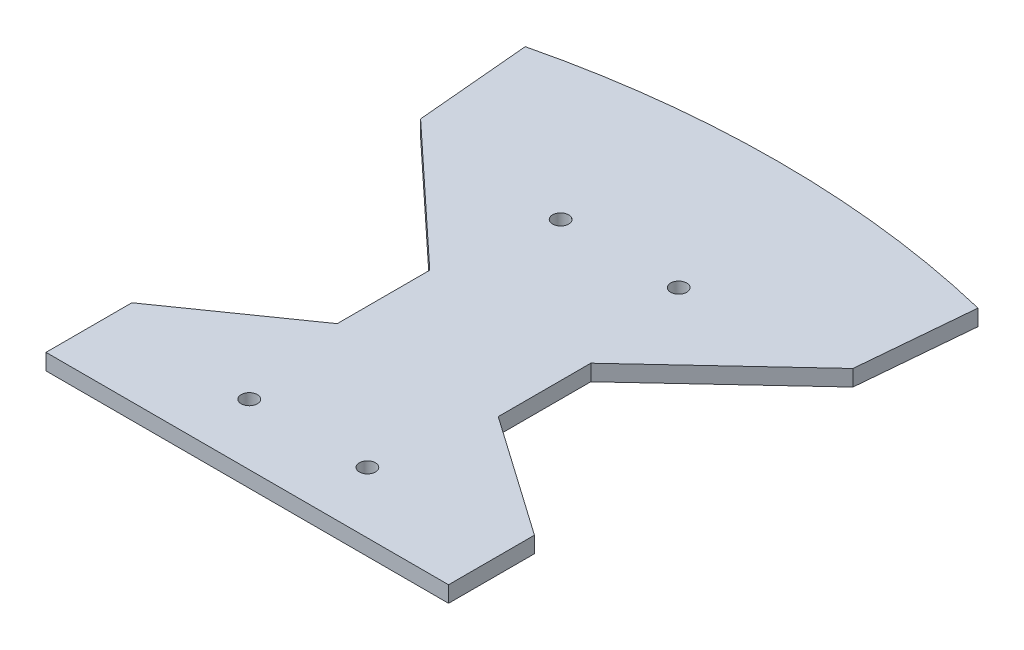
SolidWorks part; units mm, degrees
ref_plane "Front Plane" through (0, 0, 0) normal (0, 0, 1) x (1, 0, 0)
ref_plane "Top Plane" through (0, 0, 0) normal (0, 1, 0) x (1, 0, 0)
ref_plane "Right Plane" through (0, 0, 0) normal (1, 0, 0) x (0, 0, -1)
sketch "Sketch2" plane through (0, 0, 0) normal (0, 1, 0) x (1, 0, 0)
  line L0 (37.5, 0) -> (37.5, 122.2467) construction
  line L1 (0, 0) -> (75, 0)
  line L11 (0, 16) -> (0, 0)
  line L15 (14.8244, 26.3801) -> (22.5, 31.7547)
  line L25 (79.6782, 93.9598) -> (77.7747, 72.5645)
  line L27 (77.7747, 72.5645) -> (52.5, 49)
  line L29 (52.5, 31.7547) -> (52.5, 49)
  line L30 (0, 16) -> (14.8244, 26.3801)
  line L35 (75, 16) -> (60.1756, 26.3801)
  line L36 (-4.6782, 93.9598) -> (-4.6782, 68.8297) construction
  line L37 (60.1756, 26.3801) -> (52.5, 31.7547)
  line L39 (22.5, 31.7547) -> (22.5, 49)
  line L40 (-2.7747, 72.5645) -> (22.5, 49)
  line L41 (-4.6782, 93.9598) -> (-2.7747, 72.5645)
  line L42 (75, 16) -> (75, 0)
  arc A5 (79.6782, 93.9598) -> (-4.6782, 93.9598) centre (37.5, -80) ccw
  dimension "D2" = 179
  dimension "D1" = 5.084
  dimension "D3" = 84.3563
extrude "Boss-Extrude1" add sketch "Sketch2" along normal blind 3
sketch "Sketch3" plane through (0, 3, 0) normal (0, 1, 0) x (1, 0, 0)
  line L0 (37.5, 0) -> (37.5, 99) construction
  line L3 (0, 0) -> (75, 0) construction
  circle A0 centre (26.5, 69.3773) radius 1.5
  circle A1 centre (48.5, 69.3773) radius 1.5
  circle A2 centre (48.5, 11.3773) radius 1.5
  circle A3 centre (26.5, 11.3773) radius 1.5
  arc A4 (79.6782, 93.9598) -> (-4.6782, 93.9598) centre (37.5, -80) ccw construction
  dimension "D3" = 3
  dimension "D4" = 58
  dimension "D6" = 22
extrude "Cut-Extrude1" cut sketch "Sketch3" against normal through all
